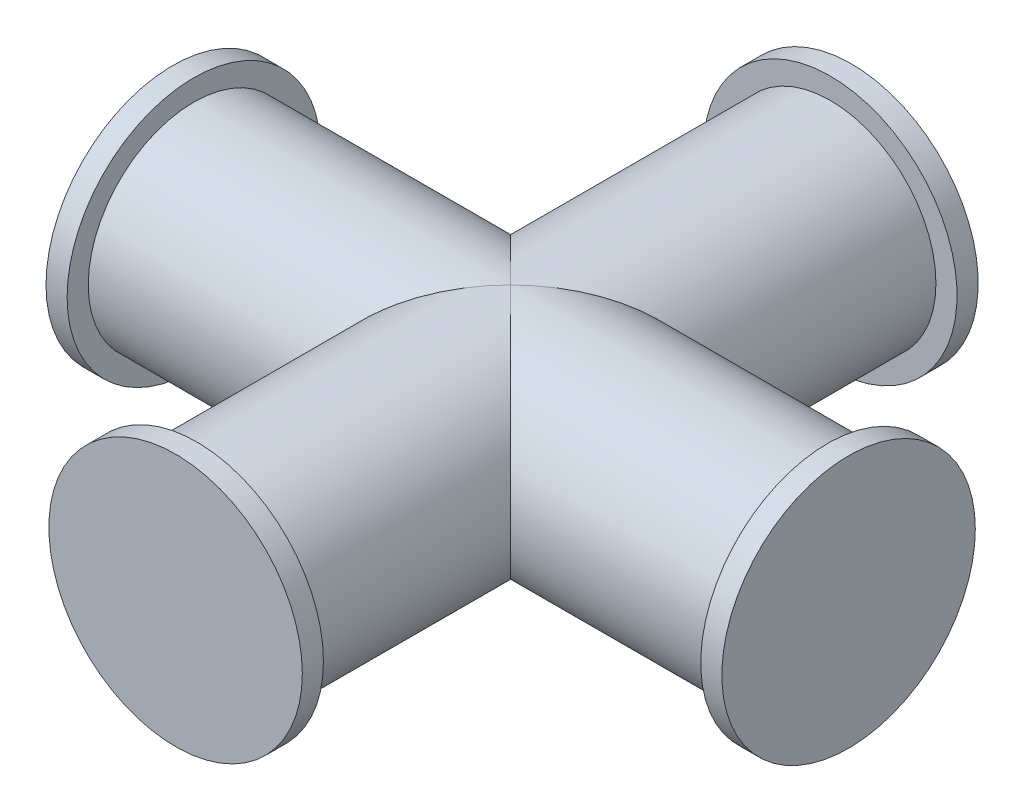
SolidWorks part; units mm, degrees
ref_plane "Front Plane" through (0, 0, 0) normal (0, 0, 1) x (1, 0, 0)
ref_plane "Top Plane" through (0, 0, 0) normal (0, 1, 0) x (1, 0, 0)
ref_plane "Right Plane" through (0, 0, 0) normal (1, 0, 0) x (0, 0, -1)
sketch "Sketch1" plane through (0, 0, 0) normal (0, 0, 1) x (1, 0, 0)
  circle A0 centre (0, 0) radius 10
  dimension "D1" = 20
extrude "Boss-Extrude1" add sketch "Sketch1" along normal blind 60
sketch "Sketch2" plane through (0, 0, 60) normal (0, 0, 1) x (1, 0, 0)
  circle A2 centre (0, 0) radius 12
  circle A3 centre (0, 0) radius 12
  dimension "D1" = 2
extrude "Boss-Extrude2" add sketch "Sketch2" along normal blind 2
sketch "Sketch3" plane through (0, 0, 0) normal (0, 0, -1) x (-1, 0, 0)
  circle A2 centre (0, 0) radius 12
  circle A3 centre (0, 0) radius 12
  dimension "D1" = 2
extrude "Boss-Extrude3" add sketch "Sketch3" along normal blind 2
sketch "Sketch4" plane through (0, 0, 0) normal (1, 0, 0) x (0, 0, -1)
  line L0 (0, 0) -> (-60.5428, 0) construction
  circle A0 centre (-30.2714, 0) radius 10
  dimension "D2" = 20
  dimension "D1" = 60.5428
extrude "Boss-Extrude4" add sketch "Sketch4" along normal mid plane 60
sketch "Sketch5" plane through (30, 0, 0) normal (1, 0, 0) x (0, 0, -1)
  circle A2 centre (-30.2714, 0) radius 12
  circle A3 centre (-30.2714, 0) radius 12
  dimension "D1" = 2
extrude "Boss-Extrude5" add sketch "Sketch5" along normal blind 2
sketch "Sketch6" plane through (-30, 0, 0) normal (-1, 0, 0) x (0, 0, 1)
  circle A2 centre (30.2714, 0) radius 12
  circle A3 centre (30.2714, 0) radius 12
  dimension "D1" = 2
extrude "Boss-Extrude6" add sketch "Sketch6" along normal blind 2
